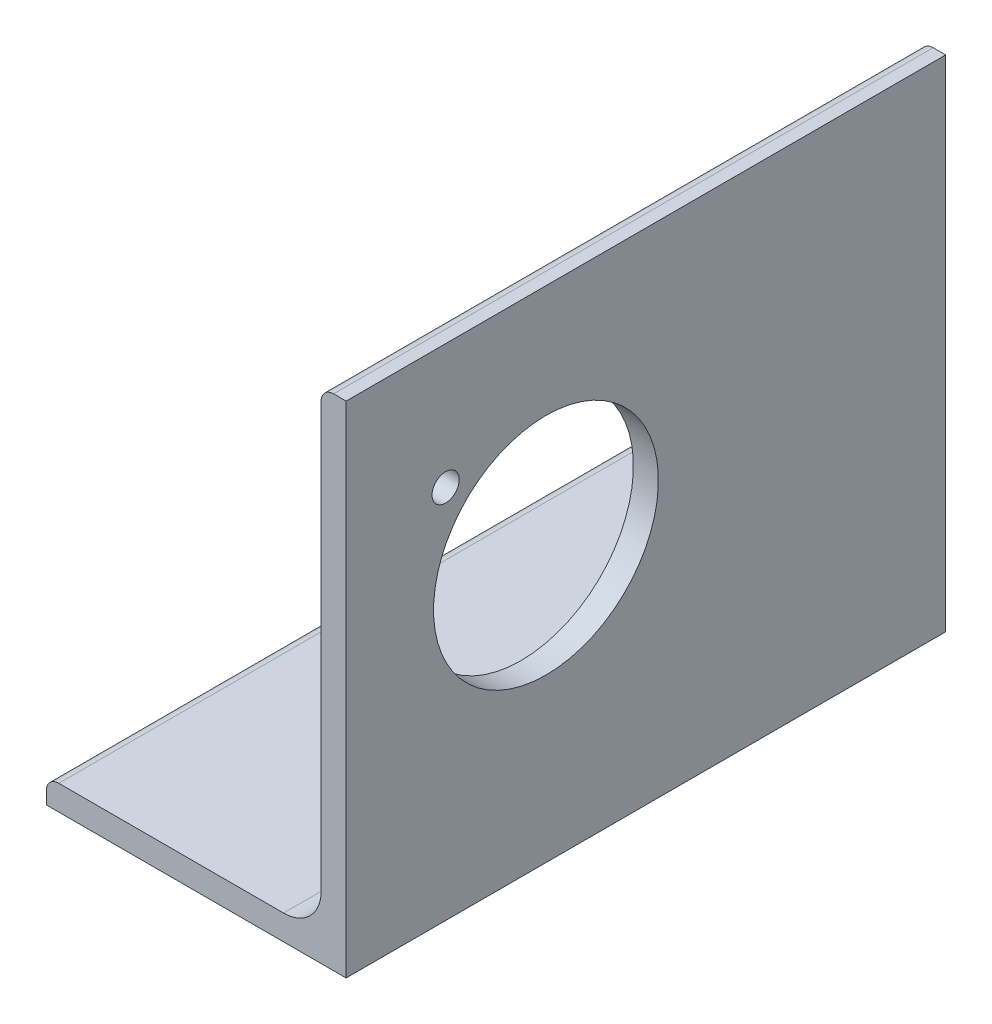
SolidWorks part; units mm, degrees
material "6061 Alloy"
ref_plane "Front Plane" through (0, 0, 0) normal (0, 0, 1) x (1, 0, 0)
ref_plane "Top Plane" through (0, 0, 0) normal (0, 1, 0) x (1, 0, 0)
ref_plane "Right Plane" through (0, 0, 0) normal (1, 0, 0) x (0, 0, -1)
sketch "Sketch0" plane through (0, 0, 0) normal (0, 0, 1) x (1, 0, 0)
  line L0 (-19.05, -31.75) -> (19.05, -31.75)
  line L1 (19.05, -31.75) -> (19.05, 31.75)
  line L2 (19.05, 0) -> (0, 0) construction
  line L3 (0, 0) -> (0, -31.75) construction
  line L4 (15.875, -23.7998) -> (15.875, 31.75) construction
  line L5 (11.0998, -28.575) -> (-19.05, -28.575) construction
  arc A0 (15.875, -23.7998) -> (11.0998, -28.575) centre (11.0998, -23.7998) cw
  point P3 (14.4764, -27.1764)
  dimension "Inside Corner Radius" = 4.7752
  dimension "Outside Height" = 63.5
  dimension "Inside Height" = 60.325
  dimension "Inside Width" = 34.925
  dimension "Wall Thickness" = 3.175
  dimension "D1" = 3.175
  dimension "Outside Width" = 38.1
sketch "Sketch1" plane through (0, 0, 0) normal (1, 0, 0) x (0, 0, -1)
  line L0 (38.1, 0) -> (-38.1, 0)
  point P4 (0, 0)
  dimension "Length" = 76.2
sketch "Sketch2" plane through (0, 0, 0) normal (0, 0, 1) x (1, 0, 0)
  line L0 (-19.05, -31.75) -> (19.05, -31.75)
  line L1 (19.05, -31.75) -> (19.05, 31.75)
  line L2 (19.05, 31.75) -> (15.875, 31.75) construction
  line L3 (15.875, 30.1625) -> (15.875, -23.7998)
  line L4 (11.0998, -28.575) -> (-17.4625, -28.575)
  line L5 (-19.05, -31.75) -> (-19.05, -28.575) construction
  line L6 (17.4625, 31.75) -> (19.05, 31.75)
  line L7 (-19.05, -30.1625) -> (-19.05, -31.75)
  line L8 (19.05, 0) -> (0, 0) construction
  line L9 (0, 0) -> (0, -31.75) construction
  arc A0 (15.875, 30.1625) -> (17.4625, 31.75) centre (17.4625, 30.1625) cw
  arc A1 (-19.05, -30.1625) -> (-17.4625, -28.575) centre (-17.4625, -30.1625) cw
  arc A2 (15.875, -23.7998) -> (11.0998, -28.575) centre (11.0998, -23.7998) cw
  dimension "Inside Radius" = 4.7752
  dimension "Height" = 63.5
  dimension "Width" = 38.1
  dimension "Thickness" = 3.175
extrude "Boss-Extrude1" add sketch "Sketch2" along normal mid plane 76.2
sketch "Break Locations" plane through (0, 0, 0) normal (1, 0, 0) x (0, 0, -1)
  line L0 (26.67, 0) -> (-26.67, 0)
  line L1 (-38.1, -31.75) -> (-38.1, 31.75) construction
  line L2 (38.1, -31.75) -> (38.1, 31.75) construction
  point P0 (15.875, 0)
  point P1 (-15.875, 0)
  point P10 (0, 0)
  point P11 (-26.67, 0)
  point P13 (26.67, 0)
  dimension "D1" = 53.975
  dimension "D2" = 53.975
  dimension "D3" = 64.77
sketch "Sketch3" plane through (15.875, 0, 0) normal (-1, 0, 0) x (0, 0, 1)
  line L0 (12.7, 3.1798) -> (25.452, 15.9317) construction
  line L1 (12.7, 3.1798) -> (38.1, 3.1813) construction
  line L2 (38.1, 30.1625) -> (38.1, -23.7998) construction
  circle A0 centre (12.7, 3.1798) radius 14.2875
  circle A1 centre (25.452, 15.9317) radius 1.7272
  dimension "D1" = 25.4
extrude "Cut-Extrude1" cut sketch "Sketch3" against normal through all
sketch "Sketch9" plane through (0, -31.75, 0) normal (0, -1, 0) x (1, 0, 0)
  line L0 (19.05, -12.7) -> (0, -12.7) construction
  line L2 (0, -12.7) -> (0, 0) construction
  line L3 (0, -12.7) -> (0, -25.4) construction
  circle A0 centre (0, 0) radius 2.4892
  circle A1 centre (0, -25.4) radius 2.4892
  dimension "D1" = 19.05
  dimension "D2" = 25.4
  dimension "D3" = 25.4
extrude "Cut-Extrude2" cut sketch "Sketch9" against normal through all
equation "\"D1@Break Locations\" = .85 * \"Height@Sketch2\""
equation "\"D2@Break Locations\"=\"D1@Break Locations\""
equation "\"Thickness@Sketch2\"=\"wall thickness@sketch0\""
equation "\"Height@Sketch2\"=\"outside height@sketch0\""
equation "\"Width@Sketch2\"=\"outside width@sketch0\""
equation "\"Inside Radius@Sketch2\"=\"inside corner radius@sketch0\""
equation "\"Length@Boss-Extrude1\"=\"length@sketch1\""
equation "\"D3@Break Locations\"=\"D2@Break Locations\"*1.2"
equation "\"D1@Sketch0\"=\"Wall Thickness@Sketch0\""
